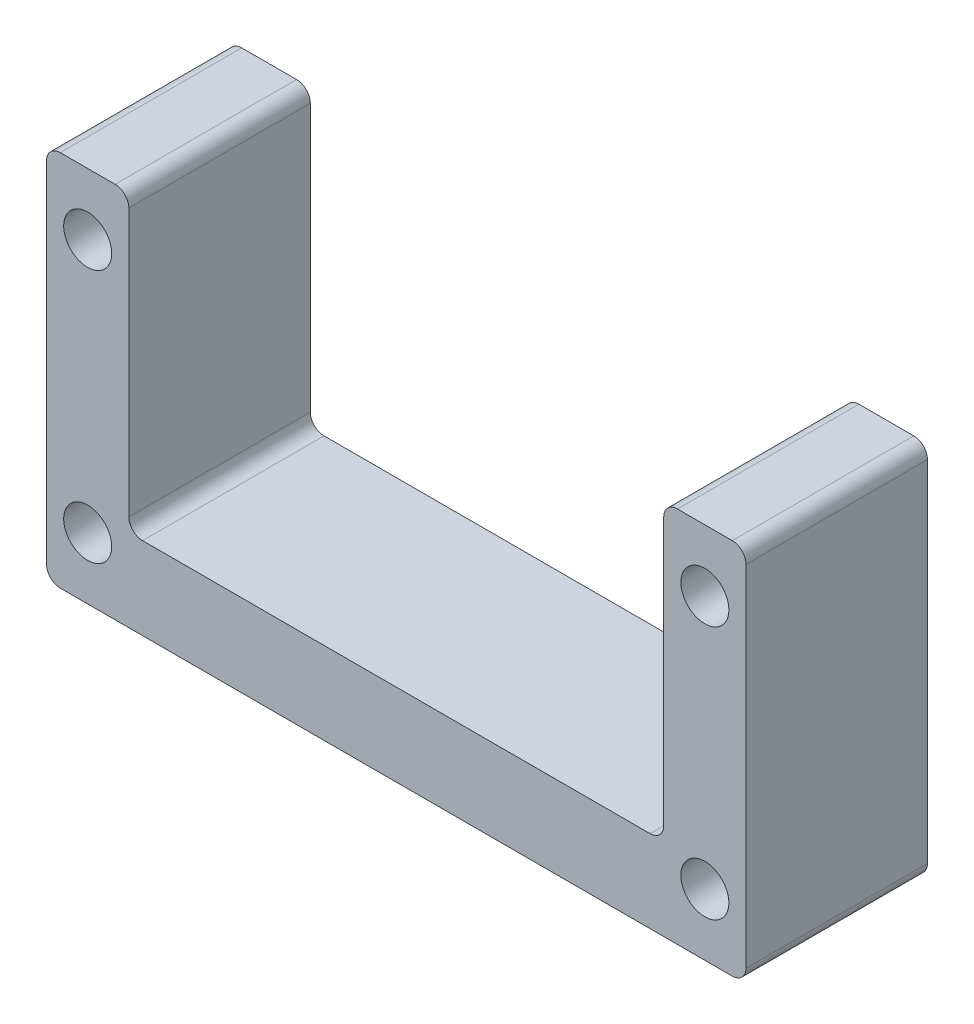
SolidWorks part; units mm, degrees
material "PLA"
ref_plane "前视基准面" through (0, 0, 0) normal (0, 0, 1) x (1, 0, 0)
ref_plane "上视基准面" through (0, 0, 0) normal (0, 1, 0) x (1, 0, 0)
ref_plane "右视基准面" through (0, 0, 0) normal (1, 0, 0) x (0, 0, -1)
sketch "草图1" plane through (0, 0, 0) normal (0, 0, 1) x (1, 0, 0)
  line L0 (-19.5, 13.75) -> (-19.5, -7.75)
  line L1 (-25.5, 13.75) -> (-19.5, 13.75)
  line L2 (-25.5, 13.75) -> (-25.5, -13.75)
  line L3 (-25.5, -13.75) -> (25.5, -13.75)
  line L4 (25.5, 13.75) -> (25.5, -13.75)
  line L5 (-25.5, 13.75) -> (25.5, -13.75) construction
  line L6 (-25.5, -13.75) -> (25.5, 13.75) construction
  line L7 (-19.5, -7.75) -> (19.5, -7.75)
  line L8 (19.5, -7.75) -> (19.5, 13.75)
  line L9 (-19.5, 13.75) -> (19.5, 13.75) construction
  line L10 (19.5, 13.75) -> (25.5, 13.75)
  line L11 (-22.5, 13.75) -> (-22.5, -13.75) construction
  line L12 (22.5, 13.75) -> (22.5, -13.75) construction
  point P0 (0, 0)
  dimension "D1" = 27.5
  dimension "D2" = 45
  dimension "D3" = 6
  dimension "D4" = 6
extrude "凸台-拉伸1" add sketch "草图1" along normal blind 13.23
sketch "草图3" plane through (0, 0, 13.23) normal (0, 0, 1) x (1, 0, 0)
  line L1 (-22.5, 9.25) -> (22.5, 9.25) construction
  line L2 (-22.5, 9.25) -> (-22.5, -9.25) construction
  line L3 (-22.5, -9.25) -> (22.5, -9.25) construction
  line L4 (22.5, 9.25) -> (22.5, -9.25) construction
  line L5 (-22.5, 9.25) -> (22.5, -9.25) construction
  line L6 (-22.5, -9.25) -> (22.5, 9.25) construction
  circle A4 centre (-22.5, 9.25) radius 1.75
  circle A5 centre (-22.5, -9.25) radius 1.75
  circle A6 centre (22.5, -9.25) radius 1.75
  circle A7 centre (22.5, 9.25) radius 1.75
  point P0 (0, 0)
  dimension "D3" = 3.5
  dimension "D1" = 18.5
  dimension "D2" = 45
extrude "切除-拉伸2" cut sketch "草图3" against normal through all
fillet "圆角1" radius 1 8 edges at (25.5, -13.75, 6.615) (-25.5, -13.75, 6.615) (-25.5, 13.75, 6.615) (-19.5, 13.75, 6.615) (-19.5, -7.75, 6.615) (19.5, -7.75, 6.615) (19.5, 13.75, 6.615) (25.5, 13.75, 6.615)
